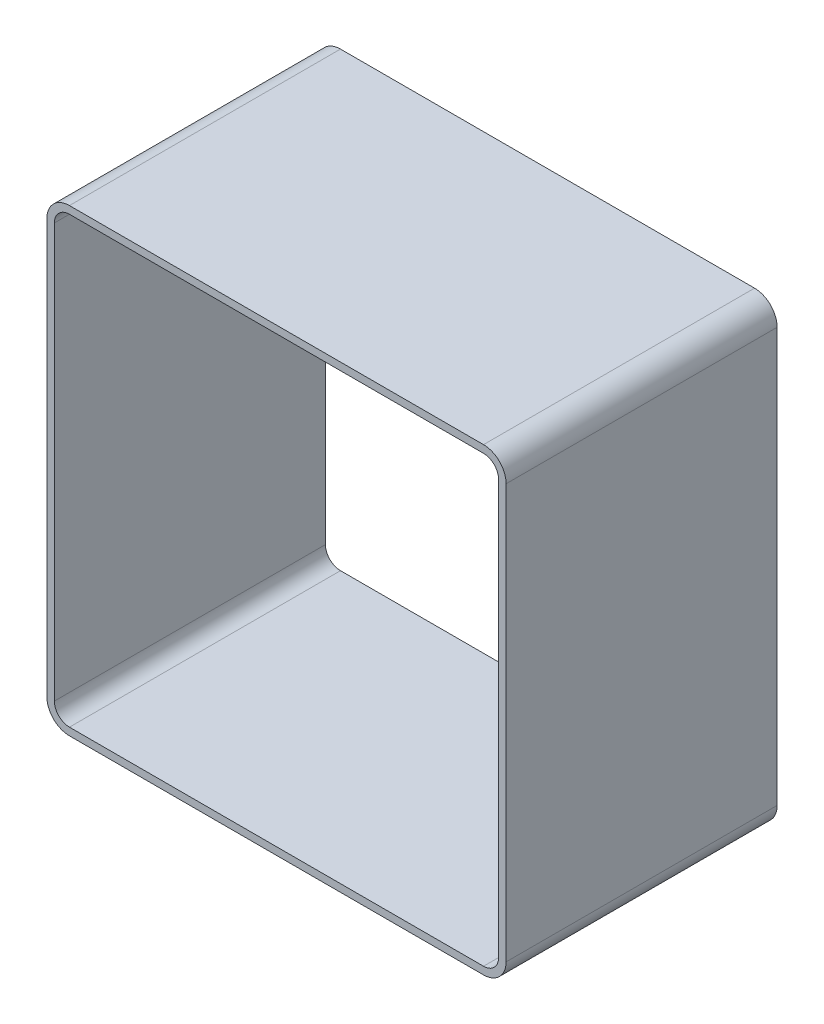
SolidWorks part; units mm, degrees
ref_plane "Plan de face" through (0, 0, 0) normal (0, 0, 1) x (1, 0, 0)
ref_plane "Plan de dessus" through (0, 0, 0) normal (0, 1, 0) x (1, 0, 0)
ref_plane "Plan de droite" through (0, 0, 0) normal (1, 0, 0) x (0, 0, -1)
sketch "Esquisse1" plane through (0, 0, 0) normal (0, 0, 1) x (1, 0, 0)
  line L1 (-152.5, -152.5) -> (152.5, -152.5)
  line L2 (-152.5, -152.5) -> (-152.5, 152.5)
  line L3 (-152.5, 152.5) -> (152.5, 152.5)
  line L4 (152.5, -152.5) -> (152.5, 152.5)
  dimension "D1" = 152.5
  dimension "D2" = 305
  dimension "D3" = 305
  dimension "D4" = 152.5
extrude "Boss.-Extru.1" add sketch "Esquisse1" along normal blind 180
sketch "Esquisse2" plane through (0, 0, 180) normal (0, 0, 1) x (1, 0, 0)
  line L0 (152.5, 152.5) -> (-152.5, 152.5) construction
  line L1 (152.5, -152.5) -> (152.5, 152.5) construction
  line L2 (-152.5, 152.5) -> (-152.5, -152.5) construction
  line L3 (-152.5, -152.5) -> (152.5, -152.5) construction
  circle A0 centre (137.5, 137.5) radius 15 construction
  circle A1 centre (137.5, -137.5) radius 15 construction
  circle A2 centre (-137.5, -137.5) radius 15 construction
  circle A3 centre (-137.5, 137.5) radius 15 construction
  circle A4 centre (137.5, 137.5) radius 10
  circle A5 centre (137.5, -137.5) radius 10
  circle A6 centre (-137.5, -137.5) radius 10
  circle A7 centre (-137.5, 137.5) radius 10
  dimension "D1" = 30
  dimension "3" = 30
  dimension "D2" = 30
  dimension "D3" = 30
  dimension "D4" = 20
  dimension "D5" = 20
  dimension "D6" = 20
  dimension "D7" = 20
extrude "Enlèv. mat.-Extru.10" cut sketch "Esquisse2" against normal blind 10
fillet "Congé2" radius 15 4 edges at (152.5, 152.5, 90) (152.5, -152.5, 90) (-152.5, -152.5, 90) (-152.5, 152.5, 90)
sketch "Esquisse3" plane through (0, 0, 180) normal (0, 0, 1) x (1, 0, 0)
  line L0 (-137.5, 147.5) -> (137.5, 147.5)
  line L1 (-147.5, 137.5) -> (-147.5, -137.5)
  line L2 (147.5, 137.5) -> (147.5, -137.5)
  line L3 (-137.5, -147.5) -> (137.5, -147.5)
  circle A0 centre (-137.5, 137.5) radius 10 construction
  circle A1 centre (137.5, 137.5) radius 10 construction
  circle A2 centre (137.5, -137.5) radius 10 construction
  arc A3 (147.5, 137.5) -> (137.5, 147.5) centre (137.5, 137.5) ccw
  arc A4 (-137.5, 147.5) -> (-147.5, 137.5) centre (-137.5, 137.5) ccw
  arc A5 (-147.5, -137.5) -> (-137.5, -147.5) centre (-137.5, -137.5) ccw
  circle A6 centre (-137.5, -137.5) radius 10 construction
  arc A7 (147.5, -137.5) -> (137.5, -147.5) centre (137.5, -137.5) cw
  point P11 (137.5, -147.5)
  point P25 (-137.5, -147.5)
  point P26 (145.8045, -131.929)
  point P27 (0, 0)
  point P28 (147.5, -137.5)
  point P29 (-137.5, 147.5)
  point P30 (147.5, 137.5)
  point P31 (127.9797, 140.56)
  point P32 (137.5, 147.5)
extrude "Enlèv. mat.-Extru.11" cut sketch "Esquisse3" against normal blind 180
